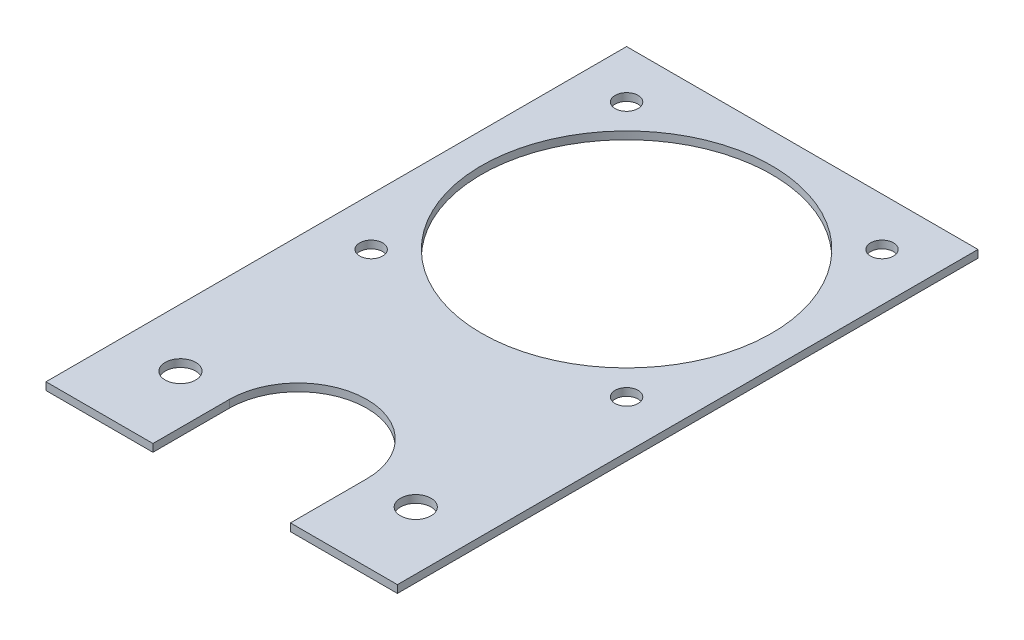
SolidWorks part; units mm, degrees
ref_plane "Спереди" through (0, 0, 0) normal (0, 0, 1) x (1, 0, 0)
ref_plane "Сверху" through (0, 0, 0) normal (0, 1, 0) x (1, 0, 0)
ref_plane "Справа" through (0, 0, 0) normal (1, 0, 0) x (0, 0, -1)
sketch "Эскиз1" plane through (0, 0, 0) normal (0, 1, 0) x (1, 0, 0)
  line L0 (-23, -28) -> (23, -28) construction
  line L1 (-23, 38) -> (23, 38)
  line L2 (-23, 38) -> (-23, -38)
  line L3 (-23, -38) -> (23, -38) construction
  line L4 (23, 38) -> (23, -38)
  line L5 (-23, 38) -> (23, -38) construction
  line L6 (-23, -38) -> (23, 38) construction
  line L7 (-20, 35) -> (20, 35)
  line L8 (-20, 35) -> (-20, -5)
  line L9 (-20, -5) -> (20, -5)
  line L10 (20, 35) -> (20, -5)
  line L11 (-20, 35) -> (20, -5) construction
  line L12 (-20, -5) -> (20, 35) construction
  line L13 (0, -38) -> (0, 38) construction
  line L14 (-8, -28) -> (-9, -28) construction
  line L15 (-9, -28) -> (-9, -38)
  line L16 (8, -28) -> (9, -28) construction
  line L17 (9, -28) -> (9, -38)
  line L18 (-23, -38) -> (-9, -38)
  line L19 (9, -38) -> (23, -38)
  circle A0 centre (0, 15) radius 19
  circle A1 centre (-16.7175, 31.7175) radius 1.5
  circle A2 centre (16.7175, 31.7175) radius 1.5
  circle A3 centre (16.7175, -1.7175) radius 1.5
  circle A4 centre (-16.7175, -1.7175) radius 1.5
  circle A5 centre (0, -28) radius 8 construction
  circle A6 centre (-15.4, -28) radius 3.75 construction
  circle A7 centre (-15.4, -28) radius 2
  circle A8 centre (15.4, -28) radius 2
  circle A9 centre (15.4, -28) radius 3.75 construction
  arc A10 (-9, -28) -> (9, -28) centre (0, -28) cw
  point P4 (0, 0)
  point P10 (0, 15)
  point P17 (-13.435, 28.435)
  point P26 (0, 15)
  dimension "D7" = 38
  dimension "D8" = 3
  dimension "D12" = 16
  dimension "D13" = 7.5
  dimension "D15" = 4
  dimension "D1" = 46
  dimension "D2" = 40
  dimension "D3" = 3
  dimension "D4" = 10
  dimension "D5" = 23
  dimension "D6" = 76
  dimension "D9" = 9.2843
  dimension "D10" = 4.6421
  dimension "D14" = 15.4
  dimension "D16" = 1
  dimension "D11" = 4
extrude "Бобышка-Вытянуть1" add sketch "Эскиз1" along normal blind 1 contours L15 A10 L17 L19 L4 L1 L2 L18 A8 A7 L7 L10 L9 L8 | L10 L7 L8 L9 A4 A3 A2 A1 A0
equation "\"D10@Эскиз1\"=\"D9@Эскиз1\"/2"
